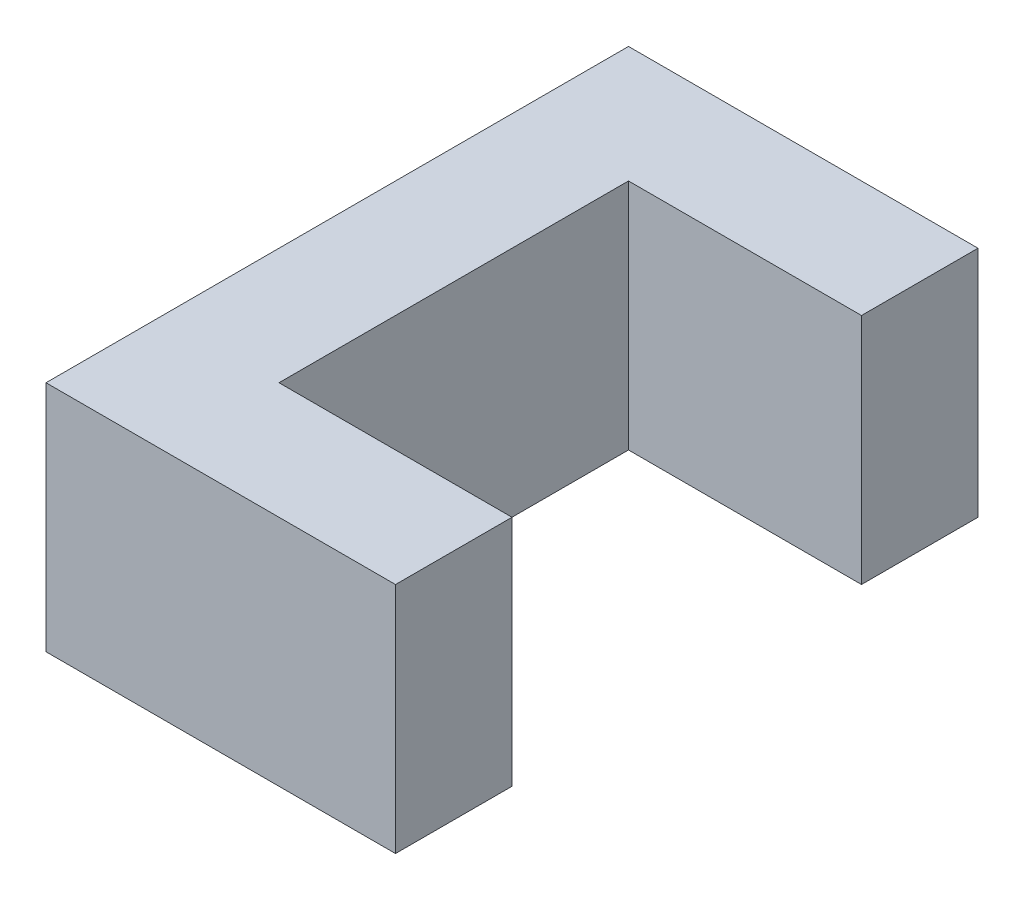
SolidWorks part; units mm, degrees
ref_plane "Přední rovina" through (0, 0, 0) normal (0, 0, 1) x (1, 0, 0)
ref_plane "Horní rovina" through (0, 0, 0) normal (0, 1, 0) x (1, 0, 0)
ref_plane "Pravá rovina" through (0, 0, 0) normal (1, 0, 0) x (0, 0, -1)
sketch "Sketch1" plane through (0, 0, 0) normal (0, 1, 0) x (1, 0, 0)
  line L0 (0, 0) -> (0, -50)
  line L1 (0, -50) -> (30, -50)
  line L2 (30, -50) -> (30, -40)
  line L3 (30, -40) -> (10, -40)
  line L4 (10, -40) -> (10, -10)
  line L5 (10, -10) -> (30, -10)
  line L6 (30, -10) -> (30, 0)
  line L7 (30, 0) -> (0, 0)
  dimension "D1" = 10
  dimension "D2" = 10
  dimension "D3" = 30
  dimension "D4" = 10
  dimension "D5" = 20
extrude "Boss-Extrude1" add sketch "Sketch1" along normal blind 20
equation "\"H\"= 30"
equation "\"D3@Sketch1\"=\"H\""
equation "\"L\"= 20"
equation "\"D5@Sketch1\"=\"L\""
